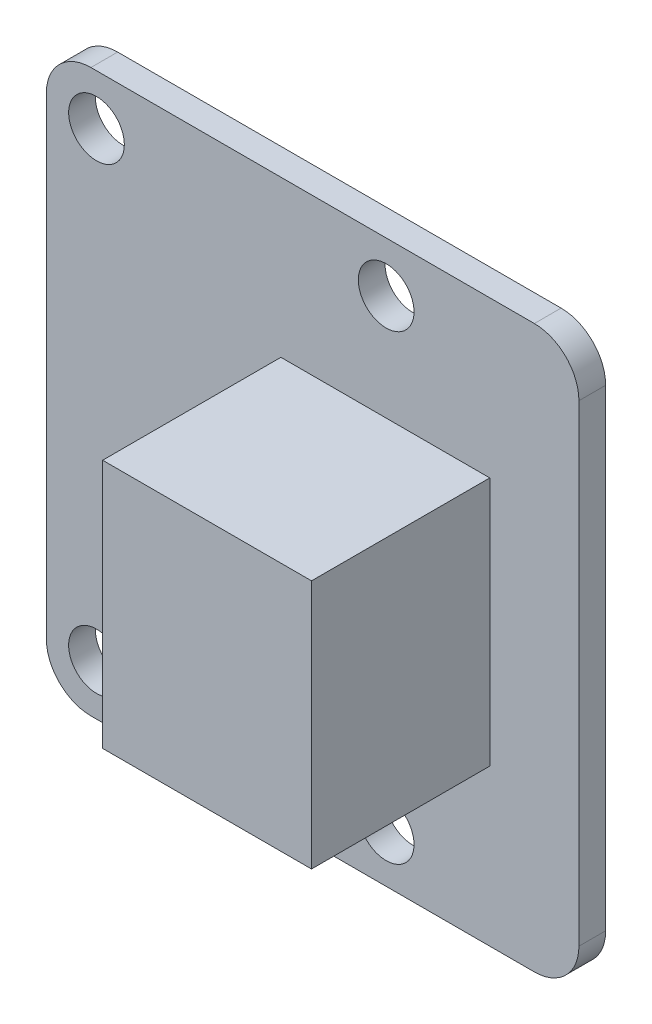
SolidWorks part; units mm, degrees
ref_plane "Alzado" through (0, 0, 0) normal (1, 0, 0) x (0, 1, 0)
ref_plane "Planta" through (0, 0, 0) normal (0, 0, 1) x (0, 1, 0)
ref_plane "Vista lateral" through (0, 0, 0) normal (0, 1, 0) x (-1, 0, 0)
sketch "Croquis1" plane through (0, 0, 0) normal (0, 0, 1) x (0, 1, 0)
  line L1 (-12.6, -11.95) -> (12.6, -11.95)
  line L2 (-12.6, -11.95) -> (-12.6, 11.95)
  line L3 (-12.6, 11.95) -> (12.6, 11.95)
  line L4 (12.6, -11.95) -> (12.6, 11.95)
  line L5 (-12.6, -11.95) -> (12.6, 11.95) construction
  line L6 (-12.6, 11.95) -> (12.6, -11.95) construction
  point P0 (0, 0)
  dimension "D1" = 25.2
  dimension "D2" = 23.9
extrude "Saliente-Extruir1" add sketch "Croquis1" along normal blind 1.2
sketch "Croquis2" plane through (0, 0, 1.2) normal (0, 0, 1) x (1, 0, 0)
  line L0 (-11.95, 12.6) -> (-11.95, -12.6) construction
  line L1 (-11.95, -12.6) -> (11.95, -12.6) construction
  line L2 (11.95, 12.6) -> (-11.95, 12.6) construction
  circle A0 centre (-9.7, -10.35) radius 1.25
  circle A1 centre (3.3, -10.35) radius 1.25
  circle A2 centre (3.3, 10.35) radius 1.25
  circle A3 centre (-9.7, 10.35) radius 1.25
  dimension "D1" = 1
  dimension "D2" = 1
  dimension "D3" = 2.5
  dimension "D6" = 1
  dimension "D7" = 10.5
  dimension "D4" = 2
  dimension "D5" = 2
extrude "Cortar-Extruir1" cut sketch "Croquis2" against normal blind 1.2
fillet "Redondeo1" radius 2 4 edges at (11.95, -12.6, 0.6) (11.95, 12.6, 0.6) (-11.95, 12.6, 0.6) (-11.95, -12.6, 0.6)
sketch "Croquis3" plane through (0, 0, 1.2) normal (0, 0, 1) x (1, 0, 0)
  line L0 (11.95, -10.6) -> (11.95, 10.6) construction
  line L1 (7.95, -5.6) -> (-1.4239, -5.6)
  line L2 (7.95, -5.6) -> (7.95, 5.6)
  line L3 (7.95, 5.6) -> (-1.4239, 5.6)
  line L4 (-1.4239, -5.6) -> (-1.4239, 5.6)
  line L5 (7.95, -5.6) -> (-1.4239, 5.6) construction
  line L6 (7.95, 5.6) -> (-1.4239, -5.6) construction
  line L7 (-9.95, -12.6) -> (9.95, -12.6) construction
  line L8 (9.95, 12.6) -> (-9.95, 12.6) construction
  point P0 (3.263, 0)
  dimension "D1" = 4
  dimension "D2" = 7
  dimension "D3" = 7
extrude "Saliente-Extruir2" add sketch "Croquis3" along normal blind 8
